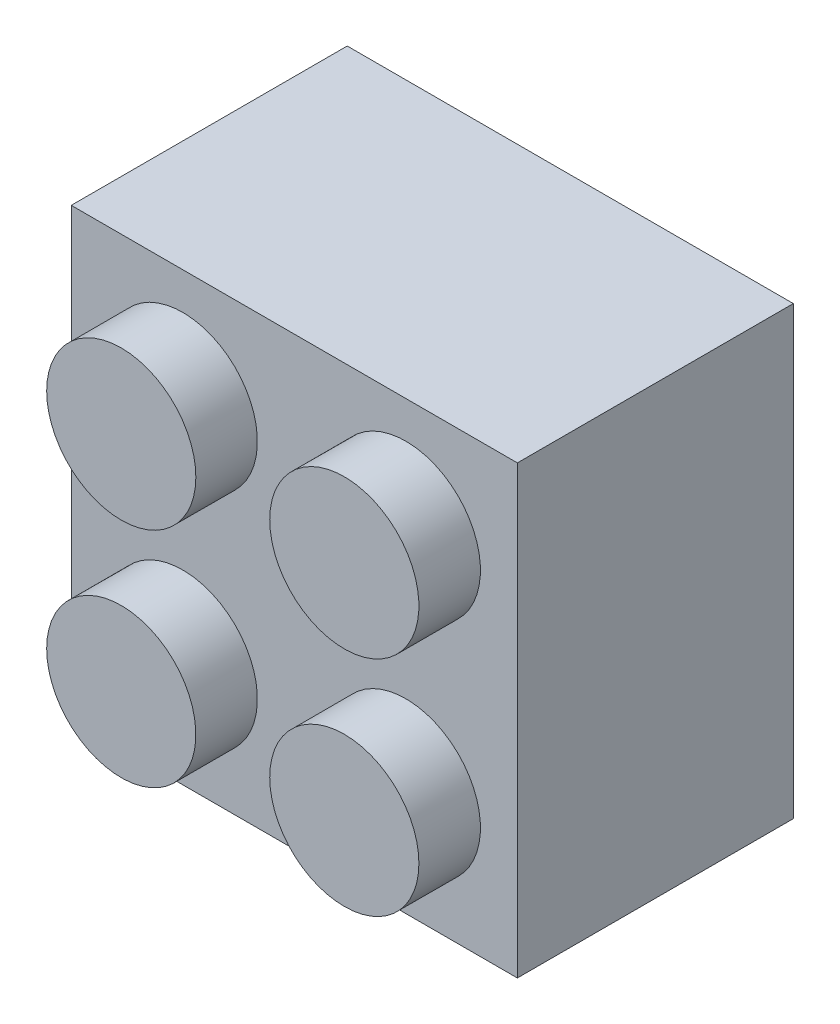
SolidWorks part; units mm, degrees
ref_plane "Plan de face" through (0, 0, 0) normal (0, 0, 1) x (1, 0, 0)
ref_plane "Plan de dessus" through (0, 0, 0) normal (0, 1, 0) x (1, 0, 0)
ref_plane "Plan de droite" through (0, 0, 0) normal (1, 0, 0) x (0, 0, -1)
sketch "Esquisse2" plane through (0, 0, 0) normal (0, 0, 1) x (1, 0, 0)
  line L0 (95.7, 95.7) -> (95.7, 0)
  line L1 (95.7, 0) -> (0, 0)
  line L3 (0, 95.7) -> (95.7, 95.7)
  line L4 (0, 95.7) -> (0, 0)
  dimension "D1" = 95.7
extrude "Boss.-Extru.1" add sketch "Esquisse2" along normal blind 59.2
sketch "Esquisse3" plane through (0, 0, 59.2) normal (0, 0, 1) x (1, 0, 0)
  line L1 (47.85, 95.7) -> (47.85, 0) construction
  line L2 (95.7, 95.7) -> (0, 95.7) construction
  line L3 (0, 0) -> (95.7, 0) construction
  line L4 (23.925, 87.775) -> (38.4351, 87.775) construction
  line L5 (23.925, 87.775) -> (23.925, 134.6265) construction
  line L6 (0, 95.7) -> (0, 0) construction
  line L7 (95.7, 0) -> (95.7, 95.7) construction
  line L8 (95.7, 47.85) -> (0, 47.85) construction
  line L9 (47.85, 95.7) -> (0, 47.85) construction
  line L10 (0, 95.7) -> (47.85, 47.85) construction
  circle A1 centre (23.925, 71.775) radius 16
  circle A2 centre (71.775, 71.775) radius 16
  circle A3 centre (71.775, 23.925) radius 16
  circle A4 centre (23.925, 23.925) radius 16
  point P0 (23.925, 71.775)
  dimension "D1" = 32
extrude "Boss.-Extru.2" add sketch "Esquisse3" along normal blind 13.2 contours A1 | A2 | A3 | A4
sketch "Esquisse4" plane through (0, 0, 0) normal (0, 0, -1) x (-1, 0, 0)
  line L0 (-87.1, 87.1) -> (-8.6, 87.1)
  line L1 (-8.6, 87.1) -> (-8.6, 8.6)
  line L2 (-8.6, 8.6) -> (-87.1, 8.6)
  line L3 (-87.1, 8.6) -> (-87.1, 87.1)
  line L4 (-95.7, 0) -> (-95.7, 95.7) construction
  line L5 (0, 95.7) -> (0, 0) construction
  line L6 (-46.7579, 95.7) -> (-46.7579, 87.1) construction
  line L7 (-95.7, 95.7) -> (0, 95.7) construction
  line L8 (-87.1, 47.85) -> (-95.7, 47.85) construction
  line L9 (-47.85, 8.6) -> (-47.85, 0) construction
  line L10 (-38.1, 41.2665) -> (-38.1, 62.0843) construction
  line L11 (-30.7, 41.2665) -> (-30.7, 65.7225) construction
  line L12 (-8.6, 47.85) -> (0, 47.85) construction
  line L13 (0, 0) -> (-95.7, 0) construction
  line L14 (0, 95.7) -> (-95.7, 0) construction
  circle A2 centre (-47.85, 47.85) radius 9.75
  circle A3 centre (-47.85, 47.85) radius 17.15
  dimension "D1" = 8.6
  dimension "D2" = 7.4
  dimension "D3" = 22.1
extrude "Enlèv. mat.-Extru.1" cut sketch "Esquisse4" against normal blind 51.1 contours L3 L2 L1 L0 A3 | A2
